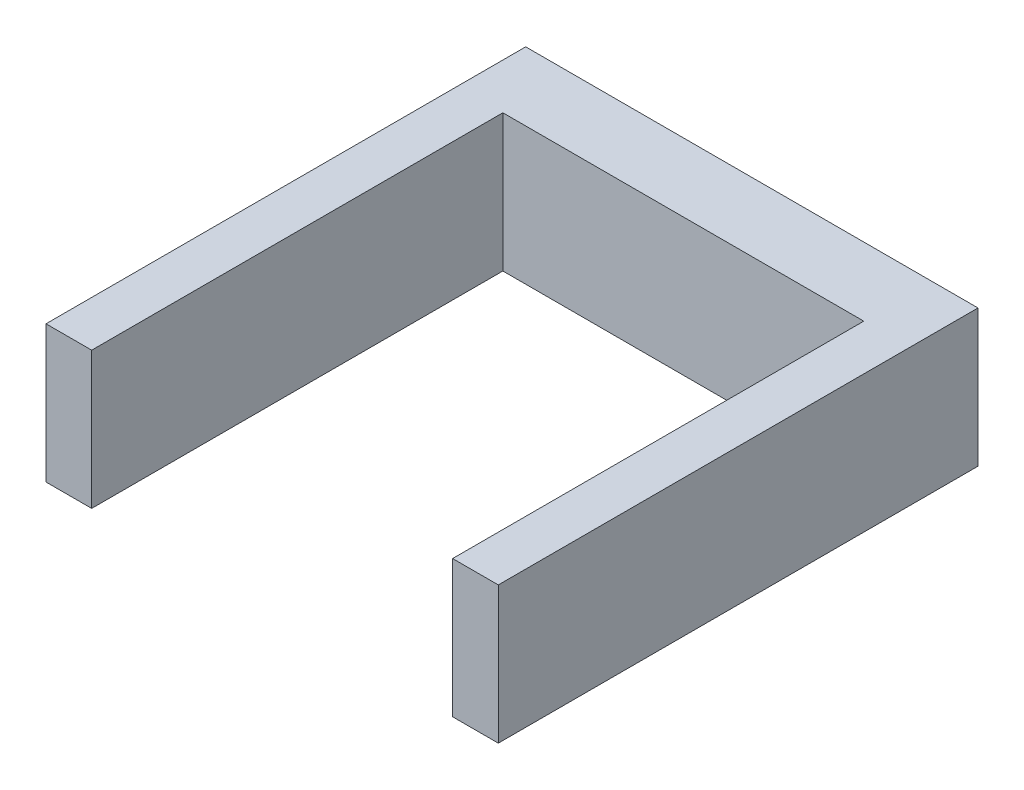
SolidWorks part; units mm, degrees
ref_plane "Front Plane" through (0, 0, 0) normal (0, 0, 1) x (1, 0, 0)
ref_plane "Top Plane" through (0, 0, 0) normal (0, 1, 0) x (1, 0, 0)
ref_plane "Right Plane" through (0, 0, 0) normal (1, 0, 0) x (0, 0, -1)
sketch "Sketch1" plane through (0, 0, 0) normal (0, 1, 0) x (1, 0, 0)
  line L0 (4.126, 9.3185) -> (4.126, 50009.3185) construction
  line L1 (-5.774, 12.3185) -> (14.026, 12.3185) construction
  line L2 (-5.774, 12.3185) -> (-5.774, 9.3185) construction
  line L3 (-5.774, 9.3185) -> (14.026, 9.3185) construction
  line L4 (14.026, 12.3185) -> (14.026, 9.3185) construction
  line L6 (-5.774, 9.3185) -> (-5.774, -8.6815) construction
  line L7 (-5.774, -8.6815) -> (-3.774, -8.6815) construction
  line L8 (-3.774, 9.3185) -> (-3.774, -8.6815) construction
  line L9 (14.026, -8.6815) -> (12.026, -8.6815) construction
  line L10 (12.026, 9.3185) -> (12.026, -8.6815) construction
  line L12 (14.026, 9.3185) -> (14.026, -8.6815) construction
  line L13 (-5.774, 12.3185) -> (-5.774, -8.6815)
  line L14 (-5.774, -8.6815) -> (-3.774, -8.6815)
  line L15 (-3.774, -8.6815) -> (-3.774, 9.3185)
  line L16 (-3.774, 9.3185) -> (12.026, 9.3185)
  line L17 (12.026, 9.3185) -> (12.026, -8.6815)
  line L18 (12.026, -8.6815) -> (14.026, -8.6815)
  line L19 (14.026, -8.6815) -> (14.026, 12.3185)
  line L20 (14.026, 12.3185) -> (-5.774, 12.3185)
  point P9 (4.126, 9.3185)
  dimension "D1" = 3
  dimension "D2" = 19.8
  dimension "D3" = 18
  dimension "D4" = 2
extrude "Boss-Extrude1" add sketch "Sketch1" along normal blind 6
